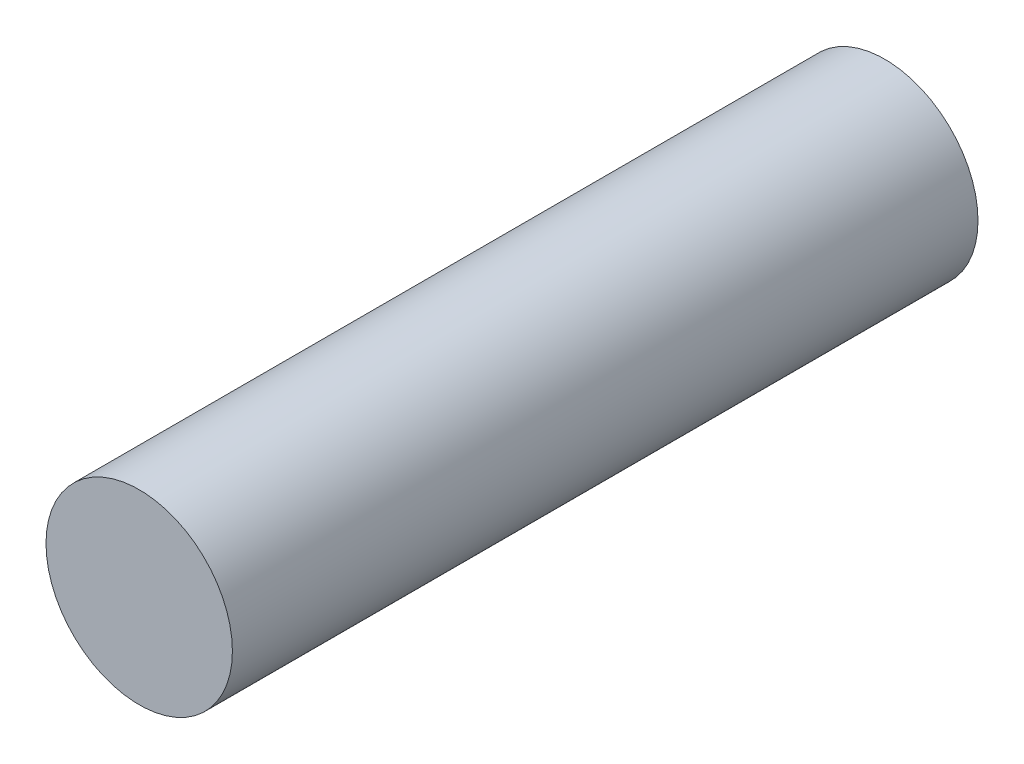
SolidWorks part; units mm, degrees
material "POM Acetal Copolymer"
ref_plane "Front Plane" through (0, 0, 0) normal (0, 0, 1) x (1, 0, 0)
ref_plane "Top Plane" through (0, 0, 0) normal (0, 1, 0) x (1, 0, 0)
ref_plane "Right Plane" through (0, 0, 0) normal (1, 0, 0) x (0, 0, -1)
sketch "Sketch1" plane through (0, 0, 0) normal (0, 0, 1) x (1, 0, 0)
  circle A0 centre (0, 0) radius 0.7938
  dimension "Diameter" = 1.5875
sketch "Sketch2" plane through (0, 0, 0) normal (1, 0, 0) x (0, 0, -1)
  line L0 (-3.175, 0) -> (3.175, 0) construction
  point P2 (0, 0)
  dimension "Length" = 6.35
sketch "Sketch3" plane through (0, 0, 0) normal (0, 0, 1) x (1, 0, 0)
  circle A0 centre (0, 0) radius 0.7938 construction
  circle A1 centre (0, 0) radius 0.7938
extrude "Boss-Extrude1" add sketch "Sketch3" along normal up to vertex (3.175 mm away) from vertex at -3.175 starting at point (0, 0, -3.175)
